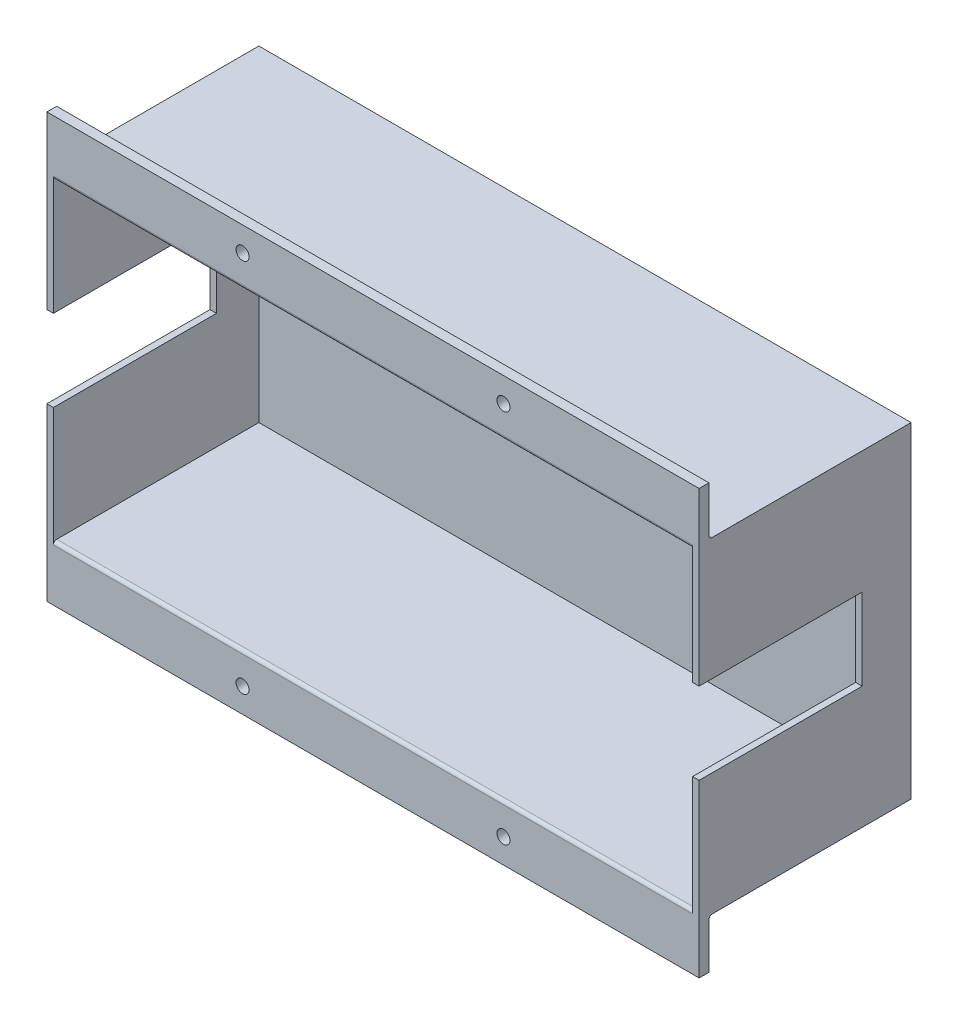
SolidWorks part; units mm, degrees
ref_plane "前视基准面" through (0, 0, 0) normal (0, 0, 1) x (1, 0, 0)
ref_plane "上视基准面" through (0, 0, 0) normal (0, 1, 0) x (1, 0, 0)
ref_plane "右视基准面" through (0, 0, 0) normal (1, 0, 0) x (0, 0, -1)
sketch "草图1" plane through (0, 0, 0) normal (0, 0, 1) x (1, 0, 0)
  line L1 (-100, 50) -> (100, 50)
  line L2 (-100, 50) -> (-100, -50)
  line L3 (-100, -50) -> (100, -50)
  line L4 (100, 50) -> (100, -50)
  line L5 (0, -50) -> (0, 50) construction
  line L6 (-100, 0) -> (100, 0) construction
  point P0 (0, 0)
  dimension "D1" = 200
  dimension "D2" = 100
extrude "凸台-拉伸1" add sketch "草图1" along normal blind 2
sketch "草图2" plane through (0, 0, 2) normal (0, 0, 1) x (1, 0, 0)
  line L0 (100, -50) -> (100, 50) construction
  line L1 (-100, 50) -> (100, 50)
  line L2 (-100, 50) -> (-100, -50)
  line L3 (-100, -50) -> (100, -50)
  line L4 (100, 50) -> (100, -50)
  line L5 (0, -50) -> (0, 50) construction
  line L6 (-100, 0) -> (100, 0) construction
  line L8 (-98, 48) -> (98, 48)
  line L9 (-98, 48) -> (-98, -48)
  line L10 (-98, -48) -> (98, -48)
  line L11 (98, 48) -> (98, -48)
  line L12 (0, -48) -> (0, 48) construction
  line L13 (-98, 0) -> (98, 0) construction
  point P0 (0, 0)
  point P6 (0, 0)
  dimension "D1" = 2
  dimension "D2" = 2
  dimension "D3" = 100
extrude "凸台-拉伸2" add sketch "草图2" along normal blind 63
sketch "草图3" plane through (0, 0, 0) normal (0, 0, -1) x (-1, 0, 0)
  line L0 (0, 0) -> (0, -24.6878) construction
  line L1 (9, 9) -> (16, 9)
  line L2 (9, 9) -> (9, -9)
  line L3 (9, -9) -> (16, -9)
  line L4 (16, 9) -> (16, -9)
  line L5 (12.5, -9) -> (12.5, 9) construction
  line L6 (9, 0) -> (16, 0) construction
  line L7 (-9, -9) -> (-16, -9)
  line L8 (-16, 9) -> (-16, -9)
  line L9 (-9, 9) -> (-16, 9)
  line L10 (-9, 9) -> (-9, -9)
  point P0 (12.5, 0)
  point P6 (0, 0)
  dimension "D1" = 7
  dimension "D2" = 18
  dimension "D3" = 9
extrude "切除-拉伸1" cut sketch "草图3" against normal blind 63
sketch "草图4" plane through (0, 0, 65) normal (0, 0, 1) x (1, 0, 0)
  line L0 (100, -50) -> (100, 50) construction
  line L1 (-100, 65) -> (100, 65)
  line L2 (-100, 65) -> (-100, 50)
  line L3 (-100, -65) -> (100, -65)
  line L4 (100, 65) -> (100, 50)
  line L5 (0, -65) -> (0, -50) construction
  line L6 (-100, 0) -> (100, 0) construction
  line L7 (100, 50) -> (-100, 50) construction
  line L8 (-100, 50) -> (100, 50)
  line L9 (-100, -50) -> (100, -50)
  line L10 (100, -50) -> (100, -65)
  line L11 (0, 50) -> (0, 65) construction
  line L12 (-100, -50) -> (-100, -65)
  point P0 (0, 0)
  dimension "D1" = 15
extrude "凸台-拉伸3" add sketch "草图4" against normal blind 3
sketch "草图5" plane through (0, 0, 0) normal (1, 0, 0) x (0, 0, -1)
  line L0 (-62, 60) -> (-52, 50)
  line L1 (-62, 50) -> (-62, 65) construction
  line L2 (-52, 50) -> (-62, 50)
  line L3 (-62, 50) -> (-62, 60)
  line L4 (0, 0) -> (33.9665, 0) construction
  line L5 (-52, -50) -> (-62, -50)
  line L6 (-62, -60) -> (-52, -50)
  line L7 (-62, -50) -> (-62, -60)
  dimension "D1" = 10
extrude "凸台-拉伸4" add sketch "草图5" along normal blind 5
pattern_linear "阵列(线性)1" count 2 spacing 80 along (-1, 0, 0) of "凸台-拉伸4"
pattern_linear "阵列(线性)2" count 2 spacing 80 along (1, 0, 0) of "凸台-拉伸4"
sketch "草图6" plane through (0, 0, 62) normal (0, 0, -1) x (-1, 0, 0)
  line L0 (-100, -65) -> (-100, -50) construction
  line L1 (0, 0) -> (0, -35.408) construction
  line L2 (0, 0) -> (38.495, 0) construction
  circle A0 centre (-40, -57.5) radius 2
  circle A1 centre (40, -57.5) radius 2
  circle A2 centre (40, 57.5) radius 2
  circle A3 centre (-40, 57.5) radius 2
  point P5 (-100, -57.5)
  dimension "D1" = 4
  dimension "D2" = 40
extrude "切除-拉伸2" cut sketch "草图6" against normal blind 5
fillet "圆角1" radius 1 8 edges at (0, -48, 65) (-37.5, -50, 62) (42.5, -50, 62) (92.5, -50, 62) (0, 48, 65) (-37.5, 50, 62) (42.5, 50, 62) (92.5, 50, 62)
sketch "草图7" plane through (100, 0, 0) normal (1, 0, 0) x (0, 0, -1)
  line L0 (-65, -65) -> (-65, 65) construction
  line L1 (-65, 12.5) -> (-15, 12.5)
  line L2 (-65, 12.5) -> (-65, -12.5)
  line L3 (-65, -12.5) -> (-15, -12.5)
  line L4 (-15, 12.5) -> (-15, -12.5)
  point P6 (-65, 0)
  dimension "D1" = 50
  dimension "D2" = 25
extrude "切除-拉伸3" cut sketch "草图7" against normal blind 281
